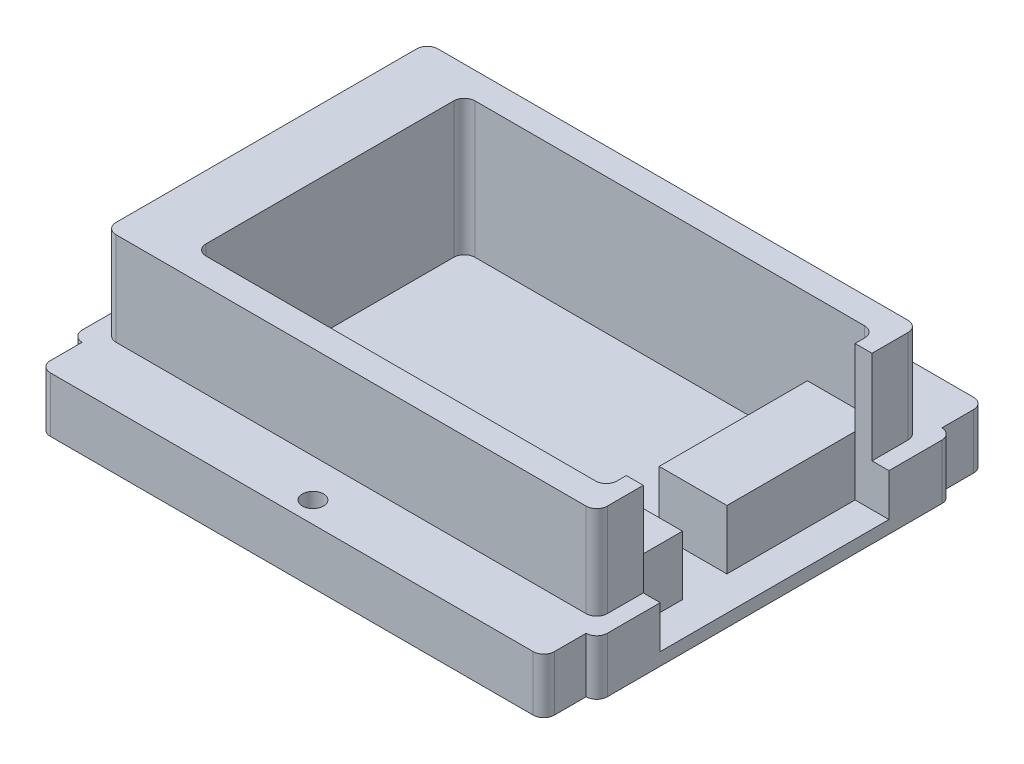
SolidWorks part; units mm, degrees
ref_plane "Front Plane" through (0, 0, 0) normal (0, 0, 1) x (1, 0, 0)
ref_plane "Top Plane" through (0, 0, 0) normal (0, 1, 0) x (1, 0, 0)
ref_plane "Right Plane" through (0, 0, 0) normal (1, 0, 0) x (0, 0, -1)
sketch "Sketch1" plane through (0, 0, 0) normal (0, 1, 0) x (1, 0, 0)
  line L1 (-62, 42) -> (62, 42)
  line L2 (-62, 42) -> (-62, -42)
  line L3 (-62, -42) -> (62, -42)
  line L4 (62, 42) -> (62, -42)
  line L5 (-62, 42) -> (62, -42) construction
  line L6 (-62, -42) -> (62, 42) construction
  point P0 (0, 0)
  dimension "D1" = 84
  dimension "D2" = 124
extrude "Boss-Extrude1" add sketch "Sketch1" along normal blind 35
sketch "Sketch2" plane through (0, 35, 0) normal (0, 1, 0) x (1, 0, 0)
  line L5 (62, 42) -> (-62, 42) construction
  line L6 (-43, 31.75) -> (54, 31.75)
  line L9 (-43, 31.75) -> (-43, -31.75)
  line L10 (-43, -31.75) -> (54, -31.75)
  line L11 (54, 31.75) -> (54, -31.75)
  line L12 (-62, -42) -> (62, -42) construction
  line L13 (62, -42) -> (62, 42) construction
  line L14 (-62, 42) -> (-62, -42) construction
  point P0 (0, 0)
  dimension "D1" = 10.25
  dimension "D2" = 10.25
  dimension "D3" = 8
  dimension "D4" = 19
extrude "Cut-Extrude1" cut sketch "Sketch2" against normal blind 32
sketch "Sketch4" plane through (0, 35, 0) normal (0, 1, 0) x (1, 0, 0)
  line L8 (62, 27) -> (54, 27)
  line L9 (62, -42) -> (62, 42) construction
  line L10 (54, -31.75) -> (54, 31.75) construction
  line L11 (54, 27) -> (54, -27)
  line L12 (54, -27) -> (62, -27)
  line L13 (62, -27) -> (62, 27)
  line L14 (62, 42) -> (-62, 42) construction
  line L15 (-62, -42) -> (62, -42) construction
  dimension "D1" = 15
  dimension "D2" = 15
extrude "Cut-Extrude2" cut sketch "Sketch4" against normal blind 32
fillet "Fillet2" radius 2.5 4 edges at (54, 19, -31.75) (-43, 19, -31.75) (54, 19, 31.75) (-43, 19, 31.75)
sketch "Sketch6" plane through (0, 35, 0) normal (0, 1, 0) x (1, 0, 0)
  line L0 (-62, 42) -> (62, 42)
  line L1 (62, 42) -> (62, 27)
  line L2 (62, 27) -> (58, 27)
  line L3 (62, 27) -> (54, 27) construction
  line L4 (58, 27) -> (58, 38)
  line L5 (58, 38) -> (-58, 38)
  line L6 (-58, 38) -> (-58, -38)
  line L7 (-58, -38) -> (58, -38)
  line L8 (58, -38) -> (58, -27)
  line L9 (54, -27) -> (62, -27) construction
  line L10 (58, -27) -> (62, -27)
  line L11 (62, -27) -> (62, -42)
  line L12 (62, -42) -> (-62, -42)
  line L13 (-62, -42) -> (-62, 42)
  dimension "D1" = 4
  dimension "D2" = 4
  dimension "D3" = 4
extrude "Cut-Extrude3" cut sketch "Sketch6" against normal blind 22
fillet "Fillet4" radius 2.5 8 edges at (-58, 24, -38) (-62, 6.5, -42) (58, 24, -38) (62, 6.5, -42) (62, 6.5, 42) (58, 24, 38) (-58, 24, 38) (-62, 6.5, 42)
sketch "Sketch9" plane through (0, 0, -42) normal (0, 0, -1) x (-1, 0, 0)
  line L6 (-59.5, 13) -> (59.5, 13)
  line L7 (-59.5, 13) -> (-59.5, 0)
  line L8 (-59.5, 0) -> (59.5, 0)
  line L9 (59.5, 13) -> (59.5, 0)
extrude "Boss-Extrude3" add sketch "Sketch9" along normal blind 10
sketch "Sketch11" plane through (0, 0, 42) normal (0, 0, 1) x (1, 0, 0)
  line L1 (-59.5, 0) -> (59.5, 0)
  line L2 (-59.5, 0) -> (-59.5, 13)
  line L3 (-59.5, 13) -> (59.5, 13)
  line L4 (59.5, 0) -> (59.5, 13)
extrude "Boss-Extrude4" add sketch "Sketch11" along normal blind 10
sketch "Sketch12" plane through (0, 13, 0) normal (0, 1, 0) x (1, 0, 0)
  line L0 (-59.5, 52) -> (59.5, 52) construction
  line L1 (59.5, -52) -> (-59.5, -52) construction
  line L2 (-62, 39.5) -> (-62, -39.5) construction
  circle A0 centre (0, 47) radius 2.5
  circle A1 centre (0, -47) radius 2.5
  point P10 (0, 0)
  dimension "D1" = 5
  dimension "D3" = 5
  dimension "D4" = 5
  dimension "D2" = 5
  dimension "D5" = 62
extrude "Cut-Extrude6" cut sketch "Sketch12" against normal through all
fillet "Fillet5" radius 2.5 4 edges at (-59.5, 6.5, -52) (-59.5, 6.5, 52) (59.5, 6.5, -52) (59.5, 6.5, 52)
sketch "Sketch13" plane through (0, 3, 0) normal (0, 1, 0) x (1, 0, 0)
  line L0 (51.5, 31.75) -> (-40.5, 31.75) construction
  line L2 (38, 31.75) -> (38, -3.25)
  line L3 (38, -3.25) -> (54, -3.25)
  line L5 (-40.5, -31.75) -> (51.5, -31.75) construction
  line L7 (38, -31.75) -> (38, -13.75)
  line L8 (38, -13.75) -> (54, -13.75)
  line L10 (54, -27) -> (54, -13.75)
  line L11 (54, -29.25) -> (54, -27) construction
  line L12 (38, -31.75) -> (51.5, -31.75)
  line L13 (54, -29.25) -> (54, -27)
  line L16 (54, 27) -> (54, 29.25) construction
  line L17 (51.5, 31.75) -> (38, 31.75)
  line L18 (54, 27) -> (54, 29.25)
  line L19 (54, 27) -> (54, -3.25)
  arc A0 (51.5, -31.75) -> (54, -29.25) centre (51.5, -29.25) ccw construction
  arc A1 (51.5, -31.75) -> (54, -29.25) centre (51.5, -29.25) ccw
  arc A3 (54, 29.25) -> (51.5, 31.75) centre (51.5, 29.25) ccw construction
  arc A4 (54, 29.25) -> (51.5, 31.75) centre (51.5, 29.25) ccw
  dimension "D2" = 35
  dimension "D3" = 18
  dimension "D4" = 16
extrude "Boss-Extrude5" add sketch "Sketch13" along normal blind 14
